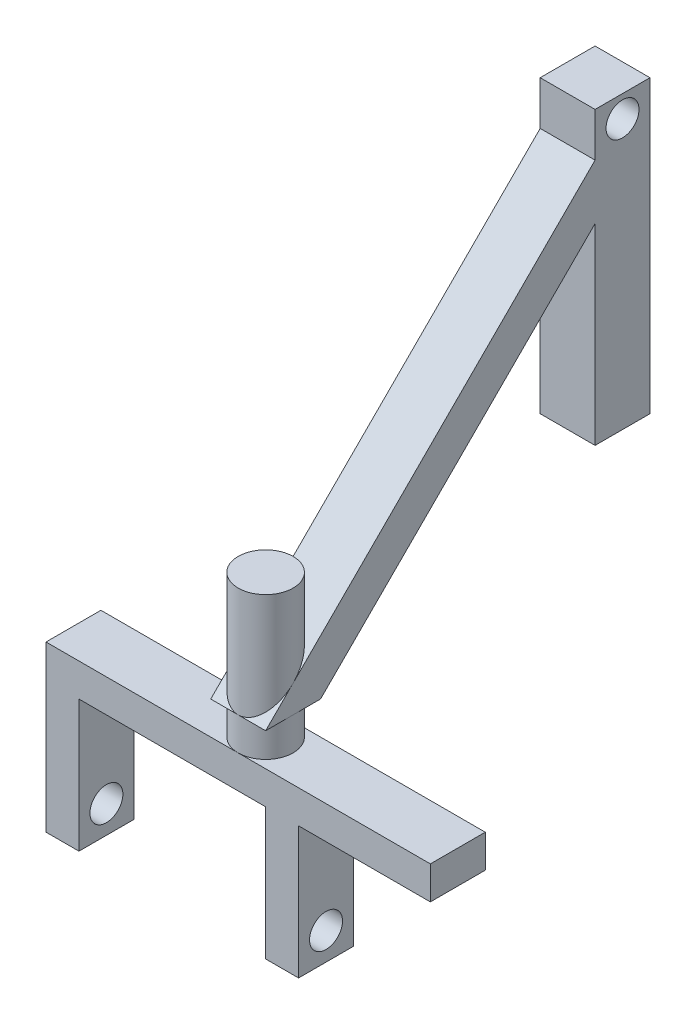
SolidWorks part; units mm, degrees
ref_plane "Front Plane" through (0, 0, 0) normal (0, 0, 1) x (1, 0, 0)
ref_plane "Top Plane" through (0, 0, 0) normal (0, 1, 0) x (1, 0, 0)
ref_plane "Right Plane" through (0, 0, 0) normal (1, 0, 0) x (0, 0, -1)
sketch "Sketch1" plane through (0, 0, 0) normal (0, 0, 1) x (1, 0, 0)
  line L1 (0, 0) -> (50, 0)
  line L2 (0, 0) -> (0, 300)
  line L3 (0, 300) -> (50, 300)
  line L4 (50, 0) -> (50, 300)
  dimension "D1" = 300
  dimension "D2" = 50
extrude "Boss-Extrude1" add sketch "Sketch1" along normal blind 50
sketch "Sketch2" plane through (0, 0, 0) normal (-1, 0, 0) x (0, 0, 1)
  line L1 (50, 300) -> (0, 343.1066)
  line L3 (0, 343.1066) -> (0, 300)
  line L5 (0, 300) -> (50, 300)
  line L9 (50, 0) -> (347.9292, 0)
  line L10 (347.9292, 0) -> (50, 300)
  line L11 (0, 0) -> (0, -26.0965)
  line L12 (0, 300) -> (347.9292, 0)
  line L14 (0, 0) -> (50, 0)
  line L20 (0, 0) -> (50, 0)
  line L21 (0, 0) -> (0, 75)
  line L22 (0, 75) -> (50, 75)
  line L23 (50, 0) -> (50, 75)
  line L24 (50, 0) -> (50, 300)
  line L26 (50, 0) -> (347.9292, 0)
  line M8 (0, 300) -> (0, 0)
  line M9 (0, 0) -> (50, 0)
  line M10 (50, 0) -> (50, 300)
  dimension "D1" = 422.8023
  dimension "D4" = 75
extrude "Cut-Extrude3" cut sketch "Sketch2" against normal blind 50 contours L22 M8 M9 M10
sketch "Sketch4" plane through (0, 0, 0) normal (-1, 0, 0) x (0, 0, 1)
  line L1 (350, 0) -> (50, 300)
  line L4 (350, 0) -> (300, 0)
  line L6 (300, 0) -> (0, 300)
  line L7 (50, 300) -> (0, 344.957)
  line L14 (0, 300) -> (0, 344.957)
  dimension "D1" = 50
extrude "Boss-Extrude2" add sketch "Sketch4" against normal blind 50
sketch "Sketch5" plane through (0, 0, 0) normal (0, -1, 0) x (1, 0, 0)
  line L0 (25, 350) -> (25, 300)
  line L1 (50, 350) -> (0, 350) construction
  line L2 (50, 300) -> (0, 300) construction
  circle A0 centre (25, 325) radius 25
extrude "Boss-Extrude3" add sketch "Sketch5" against normal blind 100 contours L0 A0 | L0 A0
sketch "Sketch6" plane through (0, 0, 0) normal (0, -1, 0) x (1, 0, 0)
  line L0 (25, 350) -> (25, 300)
  line L1 (50, 300) -> (0, 300) construction
  circle A0 centre (25, 325) radius 25
extrude "Boss-Extrude4" add sketch "Sketch6" along normal blind 60 contours L0 A0 | L0 A0
sketch "Sketch9" plane through (0, -60, 0) normal (0, -1, 0) x (1, 0, 0)
  line L1 (50, 300) -> (0, 300)
  line L3 (50, 350) -> (0, 350)
  line L5 (0, 300) -> (-150, 300)
  line L7 (0, 350) -> (-150, 350)
  line L8 (-150, 300) -> (-150, 350)
  line L9 (50, 350) -> (200, 350)
  line L11 (50, 300) -> (200, 300)
  line L12 (200, 350) -> (200, 300)
  point P0 (25, 325)
  dimension "D1" = 50
  dimension "D2" = 50
  dimension "D3" = 150
  dimension "D4" = 150
extrude "Boss-Extrude12" add sketch "Sketch9" against normal blind 30
sketch "Sketch13" plane through (-150, 0, 0) normal (-1, 0, 0) x (0, 0, 1)
  line L1 (300, -30) -> (350, -30)
  line L2 (300, -30) -> (300, -180)
  line L3 (300, -180) -> (350, -180)
  line L4 (350, -30) -> (350, -180)
  dimension "D1" = 50
  dimension "D2" = 150
extrude "Boss-Extrude13" add sketch "Sketch13" against normal blind 30
sketch "Sketch14" plane through (0, -60, 0) normal (0, -1, 0) x (1, 0, 0)
  line L0 (200, 350) -> (-120, 350) construction
  line L1 (50, 300) -> (80, 300)
  line L2 (50, 300) -> (50, 350)
  line L3 (50, 350) -> (80, 350)
  line L4 (80, 300) -> (80, 350)
  dimension "D1" = 30
extrude "Boss-Extrude14" add sketch "Sketch14" along normal blind 120
sketch "Sketch15" plane through (-150, 0, 0) normal (-1, 0, 0) x (0, 0, 1)
  line L0 (350, -30) -> (350, -180) construction
  line L1 (300, -180) -> (350, -180)
  line L2 (300, -180) -> (300, -130)
  line L3 (300, -130) -> (350, -130)
  line L4 (350, -180) -> (350, -130)
  line L5 (325, -130) -> (325, -180)
  circle A0 centre (325, -155) radius 15
  dimension "D2" = 30
  dimension "D1" = 50
extrude "Cut-Extrude4" cut sketch "Sketch15" against normal blind 290 contours L5 A0 | L5 A0
sketch "Sketch17" plane through (0, 0, 0) normal (0, 0, 1) x (1, 0, 0)
  line L1 (0, 344.957) -> (50, 344.957)
  line L2 (0, 344.957) -> (0, 300)
  line L3 (0, 300) -> (50, 300)
  line L4 (50, 344.957) -> (50, 300)
extrude "Cut-Extrude5" cut sketch "Sketch17" along normal blind 50
sketch "Sketch18" plane through (0, 300, 0) normal (0, 1, 0) x (1, 0, 0)
  line L0 (50, -50) -> (0, -50) construction
  line L1 (0, 0) -> (50, 0)
  line L2 (0, 0) -> (0, -50)
  line L3 (0, -50) -> (50, -50)
  line L4 (50, 0) -> (50, -50)
  line L5 (50, -50) -> (50, 0) construction
extrude "Boss-Extrude15" add sketch "Sketch18" along normal blind 40
sketch "Sketch19" plane through (50, 0, 0) normal (1, 0, 0) x (0, 0, -1)
  circle A0 centre (-25, 320.0762) radius 15
extrude "Cut-Extrude6" cut sketch "Sketch19" against normal blind 90
